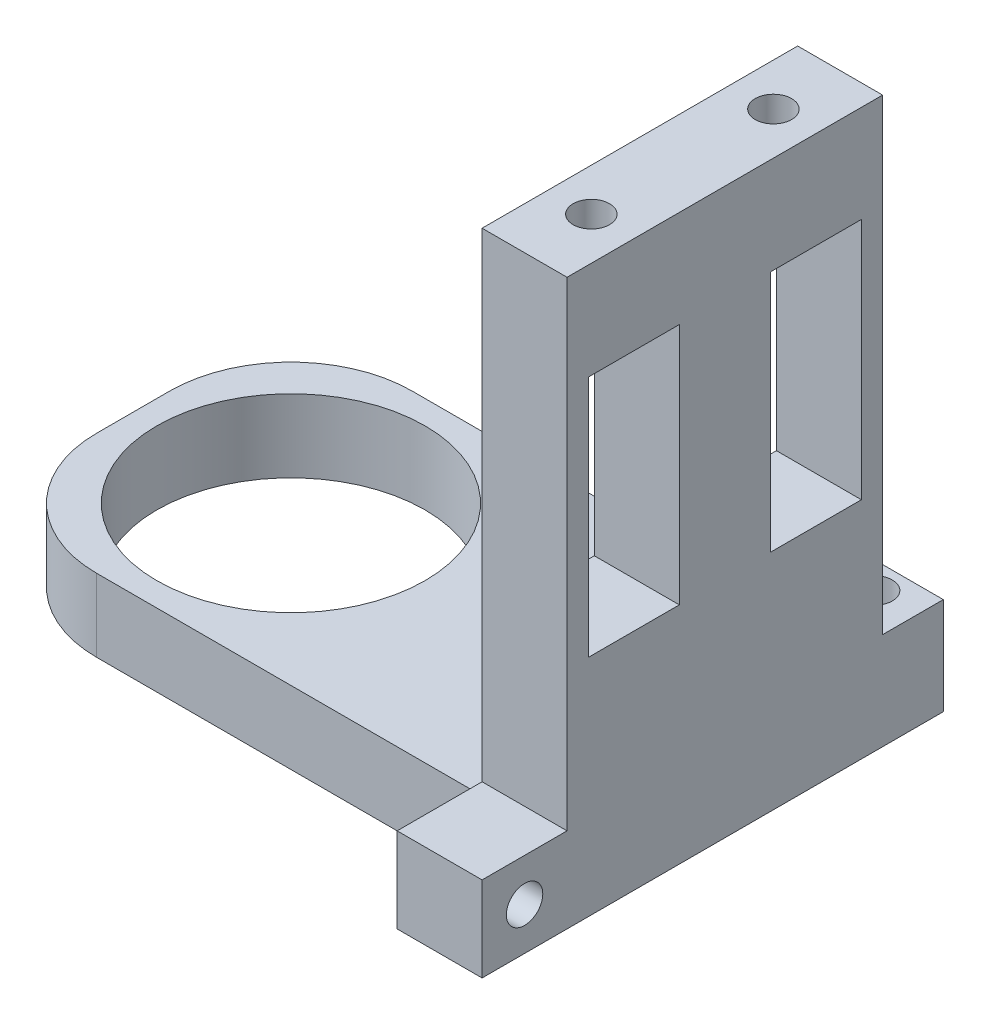
SolidWorks part; units mm, degrees
ref_plane "Спереди" through (0, 0, 0) normal (0, 0, 1) x (1, 0, 0)
ref_plane "Сверху" through (0, 0, 0) normal (0, 1, 0) x (1, 0, 0)
ref_plane "Справа" through (0, 0, 0) normal (1, 0, 0) x (0, 0, -1)
ref_plane "Плоскость4" through (24.375, 0, 0) normal (1, 0, 0) x (0, 0, -1)
sketch "Эскиз1" plane through (24.375, 0, 0) normal (1, 0, 0) x (0, 0, -1)
  line L0 (-20, 0) -> (18, 0)
  line L1 (18, 0) -> (18, 46.5)
  line L2 (18, 46.5) -> (-20, 46.5)
  line L3 (-20, 46.5) -> (-20, 0)
extrude "Бобышка-Вытянуть1" add sketch "Эскиз1" against normal blind 7
sketch "Эскиз2" plane through (17.375, 0, 0) normal (-1, 0, 0) x (0, 0, 1)
  line L0 (-13, 8) -> (-13, 46.5)
  line L1 (-13, 46.5) -> (-18, 46.5)
  line L2 (-18, 46.5) -> (-18, 8)
  line L3 (-18, 8) -> (-13, 8)
extrude "Вырез-Вытянуть1" cut sketch "Эскиз2" against normal through all
sketch "Эскиз3" plane through (17.375, 0, 0) normal (-1, 0, 0) x (0, 0, 1)
  line L0 (13, 46.5) -> (13, 7)
  line L1 (13, 7) -> (20, 7)
  line L2 (20, 7) -> (20, 46.5)
  line L3 (20, 46.5) -> (13, 46.5)
extrude "Вырез-Вытянуть2" cut sketch "Эскиз3" against normal through all
sketch "Эскиз4" plane through (24.375, 0, 0) normal (1, 0, 0) x (0, 0, -1)
  line L0 (-3.75, 38.5) -> (-11.25, 38.5)
  line L1 (-11.25, 38.5) -> (-11.25, 18.5)
  line L2 (-11.25, 18.5) -> (-3.75, 18.5)
  line L3 (-3.75, 18.5) -> (-3.75, 38.5)
extrude "Вырез-Вытянуть3" cut sketch "Эскиз4" against normal through all
sketch "Эскиз5" plane through (17.375, 0, 0) normal (-1, 0, 0) x (0, 0, 1)
  line L0 (-11.25, 18.5) -> (-3.75, 18.5)
  line L1 (-3.75, 18.5) -> (-3.75, 38.5)
  line L2 (-3.75, 38.5) -> (-11.25, 38.5)
  line L3 (-11.25, 38.5) -> (-11.25, 18.5)
extrude "Вырез-Вытянуть4" cut sketch "Эскиз5" against normal through all
sketch "Эскиз6" plane through (17.375, 0, 0) normal (-1, 0, 0) x (0, 0, 1)
  line L0 (-13, 6) -> (13, 6)
  line L1 (13, 6) -> (13, 0)
  line L2 (13, 0) -> (-13, 0)
  line L3 (-13, 0) -> (-13, 6)
extrude "Бобышка-Вытянуть2" add sketch "Эскиз6" along normal blind 41.75
hole_wizard "Диаметр отверстия Ø3.0 (3)1" positions "Эскиз8" profile "Эскиз7" hole size "Ø3.0" standard "Ansi Metric"
sketch "Эскиз8" plane through (0, 46.5, 0) normal (0, 1, 0) x (1, 0, 0)
  point P0 (20.875, -7.5)
  point P1 (20.875, 7.5)
sketch "Эскиз7" plane through (20.875, 46.5, 7.5) normal (1, 0, 0) x (0, 0, 1)
  line L0 (0, 0) -> (0, 8)
  line L1 (0, 8) -> (1.5, 8)
  line L2 (1.5, 8) -> (1.5, 0)
  line L5 (1.5, 0) -> (0, 0)
  line L11 (0, -6.35) -> (0, 107.95) construction
  dimension "Диаметр сквозного отверстия" = 3
  dimension "Глубина сквозного отверстия" = 8
hole_wizard "Диаметр отверстия Ø3.0 (3)2" positions "Эскиз10" profile "Эскиз9" hole size "Ø3.0" standard "Ansi Metric"
sketch "Эскиз10" plane through (24.375, 0, 0) normal (1, 0, 0) x (0, 0, -1)
  point P0 (-16.5, 3.5)
sketch "Эскиз9" plane through (24.375, 3.5, 16.5) normal (0, 1, 0) x (0, 0, -1)
  line L0 (0, 0) -> (0, 48.75)
  line L1 (0, 48.75) -> (1.5, 48.75)
  line L2 (1.5, 48.75) -> (1.5, 0)
  line L5 (1.5, 0) -> (0, 0)
  line L11 (0, -6.35) -> (0, 107.95) construction
  dimension "Диаметр сквозного отверстия" = 3
  dimension "Глубина сквозного отверстия" = 48.75
hole_wizard "Диаметр отверстия Ø3.0 (3)3" positions "Эскиз12" profile "Эскиз11" hole size "Ø3.0" standard "Ansi Metric"
sketch "Эскиз12" plane through (0, 8, 0) normal (0, 1, 0) x (1, 0, 0)
  point P0 (20.875, 15.8)
sketch "Эскиз11" plane through (20.875, 8, -15.8) normal (1, 0, 0) x (0, 0, 1)
  line L0 (0, 0) -> (0, 8)
  line L1 (0, 8) -> (1.5, 8)
  line L2 (1.5, 8) -> (1.5, 0)
  line L5 (1.5, 0) -> (0, 0)
  line L11 (0, -6.35) -> (0, 107.95) construction
  dimension "Диаметр сквозного отверстия" = 3
  dimension "Глубина сквозного отверстия" = 8
hole_wizard "Отверстие с зазором M201" positions "Эскиз14" profile "Эскиз13" hole size "M20" standard "Ansi Metric"
sketch "Эскиз14" plane through (0, 0, 0) normal (0, -1, 0) x (-1, 0, 0)
  point P0 (11.375, 0)
sketch "Эскиз13" plane through (-11.375, 0, 0) normal (1, 0, 0) x (0, 0, -1)
  line L0 (0, 0) -> (0, 46.5)
  line L1 (0, 46.5) -> (11.05, 46.5)
  line L2 (11.05, 46.5) -> (11.05, 0)
  line L5 (11.05, 0) -> (0, 0)
  line L11 (0, -6.35) -> (0, 107.95) construction
  dimension "Диаметр сквозного отверстия" = 22.1
  dimension "Глубина сквозного отверстия" = 46.5
fillet "Скругление1" radius 10 2 edges at (-24.375, 3, 13) (-24.375, 3, -13)
